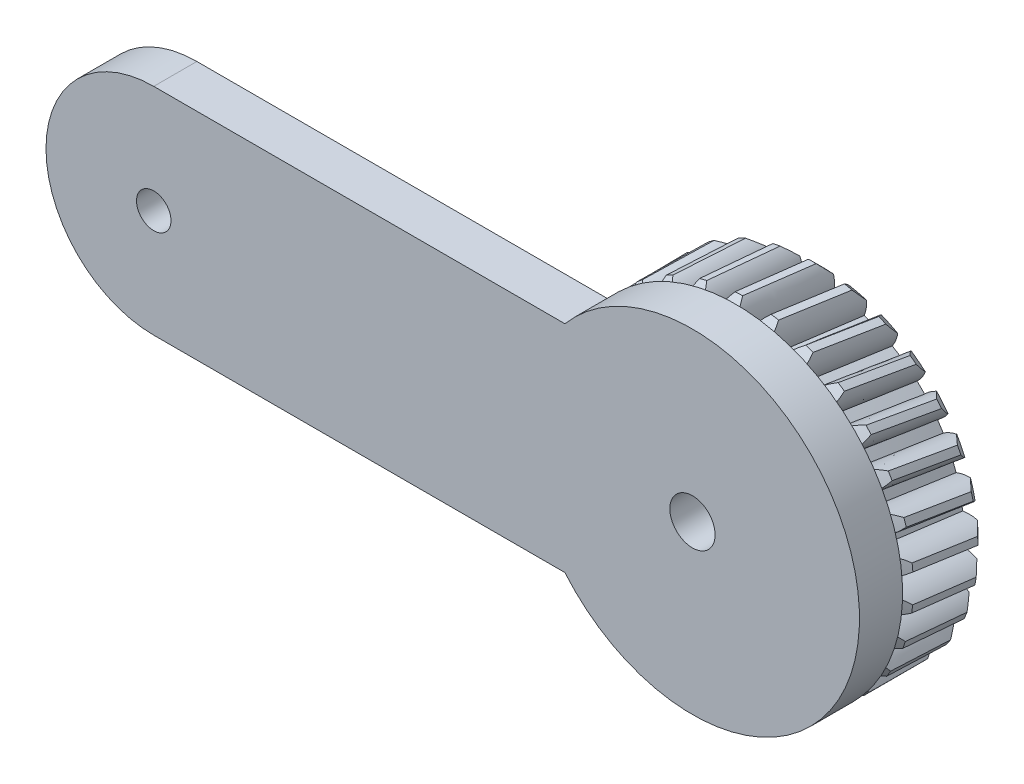
SolidWorks part; units mm, degrees
ref_plane "Front Plane" through (0, 0, 0) normal (1, 0, 0) x (0, 1, 0)
ref_plane "Top Plane" through (0, 0, 0) normal (0, 0, 1) x (0, 1, 0)
ref_plane "Right Plane" through (0, 0, 0) normal (0, 1, 0) x (-1, 0, 0)
sketch "Sketch5" plane through (0, 0, 0) normal (0, 0, 1) x (0, 1, 0)
  circle A0 centre (0, 0) radius 15.5
  dimension "D1" = 31
extrude "Boss-Extrude1" add sketch "Sketch5" along normal blind 8
chamfer "Chamfer1" distance 1 angle 45 2 edges at (15.5, 0, 8) (15.5, 0, 0)
sketch "Sketch9" plane through (0, 0, 8) normal (0, 0, 1) x (1, 0, 0)
  circle A0 centre (0, 0) radius 15.5 construction
  circle A1 centre (0, 0) radius 15.5
curve "Helix/Spiral1" pitch 704.2254 height 20 turns 0.0284
sketch "Sketch10" plane through (0, 0, 8) normal (0, 0, 1) x (1, 0, 0)
  line L0 (0, 0) -> (31, 0) construction
  line L1 (13.1433, 0.5) -> (13.1433, -0.5)
  circle A0 centre (0, 0) radius 15.5 construction
  arc A1 (15.4433, -1.325) -> (15.4433, 1.325) centre (0, 0) ccw
  arc A2 (13.1433, 0.5) -> (15.4433, 1.325) centre (13.2582, 3.798) ccw
  arc A3 (13.1433, -0.5) -> (15.4433, -1.325) centre (13.2582, -3.798) cw
  point P9 (13.1433, 0)
  dimension "D2" = 2.65
  dimension "D4" = 3.3
  dimension "D1" = 1
  dimension "D3" = 2.3
sweep "Cut-Sweep1" cut profiles "Sketch10" path "Helix/Spiral1"
pattern_circular "CirPattern1" count 29 over 360 about axis through (0, 0, 8) along (0, 0, -1) of "Cut-Sweep1"
sketch "Sketch12" plane through (0, 0, 0) normal (0, 0, 1) x (0, 1, 0)
  line L0 (0, 0) -> (0, 50) construction
  line L1 (0, 25) -> (-14.1559, 25) construction
  line L2 (10, 50) -> (10, 11.8427)
  line L3 (-10, 50) -> (-10, 11.8427)
  line L4 (-10, 11.8427) -> (10, 11.8427) construction
  arc A0 (-10, 11.8427) -> (10, 11.8427) centre (0, 0) ccw
  arc A1 (10, 50) -> (-10, 50) centre (0, 50) ccw
  circle A3 centre (0, 50) radius 1.6
  dimension "D1" = 31
  dimension "D2" = 20
  dimension "D4" = 3.2
  dimension "D3" = 50
extrude "Boss-Extrude2" add sketch "Sketch12" along normal blind 4 from surface at 8 starting at face at (0, 0, 8)
sketch "Sketch11" plane through (0, 0, 0) normal (0, 0, 1) x (0, 1, 0)
  circle A0 centre (0, 0) radius 2.1
  dimension "D1" = 4.2
extrude "Cut-Extrude1" cut sketch "Sketch11" along normal blind 15
